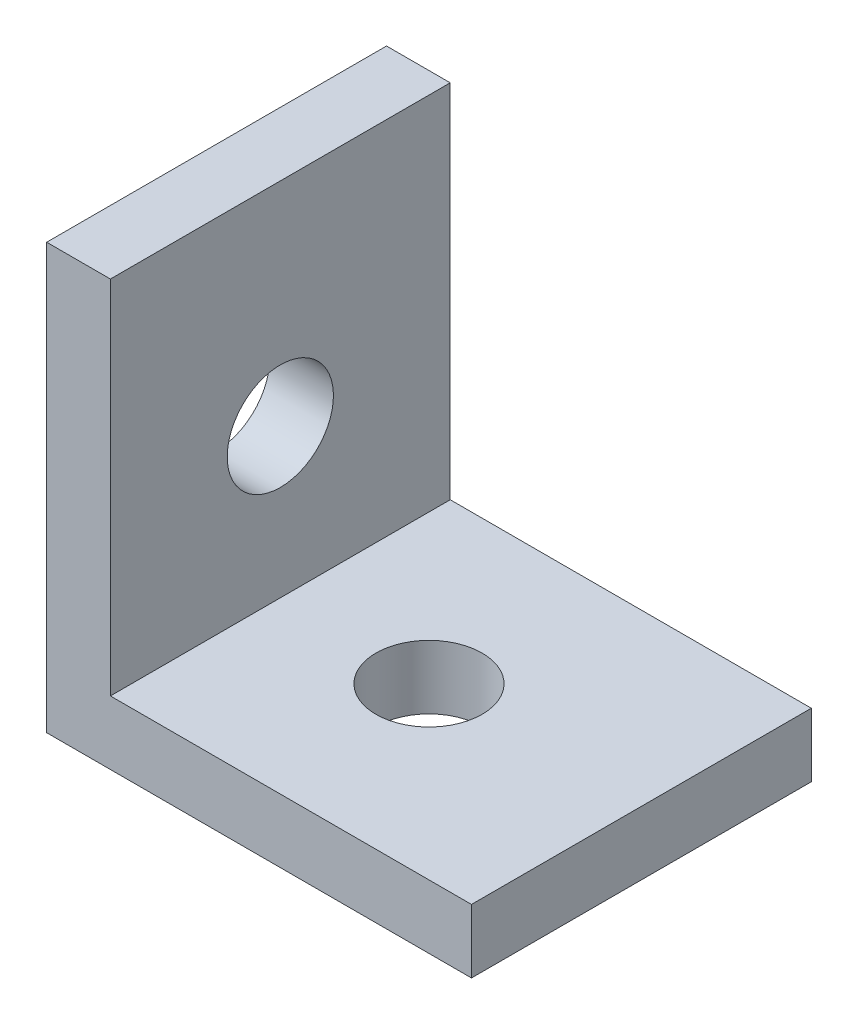
SolidWorks part; units mm, degrees
ref_plane "Front" through (0, 0, 0) normal (0, 0, 1) x (1, 0, 0)
ref_plane "Top" through (0, 0, 0) normal (0, 1, 0) x (1, 0, 0)
ref_plane "Right" through (0, 0, 0) normal (1, 0, 0) x (0, 0, -1)
sketch "Sketch1" plane through (0, 0, 0) normal (0, 0, 1) x (1, 0, 0)
  line L0 (0, 0) -> (0, 17)
  line L1 (0, 17) -> (-3, 17)
  line L2 (-3, 17) -> (-3, -3)
  line L3 (-3, -3) -> (17, -3)
  line L4 (17, -3) -> (17, 0)
  line L5 (17, 0) -> (0, 0)
  dimension "D1" = 3
  dimension "D2" = 20
extrude "Boss-Extrude1" add sketch "Sketch1" along normal blind 16
sketch "Sketch2" plane through (-3, 0, 0) normal (-1, 0, 0) x (0, 0, 1)
  line L0 (8, 7) -> (8, 17) construction
  line L1 (16, 17) -> (0, 17) construction
  line L2 (8, 7) -> (8, -3) construction
  line L3 (16, -3) -> (0, -3) construction
  circle A0 centre (8, 7) radius 2.5
  dimension "D1" = 5
extrude "Cut-Extrude1" cut sketch "Sketch2" against normal up to next
sketch "Sketch3" plane through (0, -3, 0) normal (0, -1, 0) x (1, 0, 0)
  line L0 (-3, 8) -> (7, 8) construction
  line L1 (-3, 16) -> (-3, 0) construction
  line L2 (7, 8) -> (17, 8) construction
  line L3 (17, 16) -> (17, 0) construction
  circle A0 centre (7, 8) radius 2.5
  dimension "D1" = 5
extrude "Cut-Extrude2" cut sketch "Sketch3" against normal up to next
